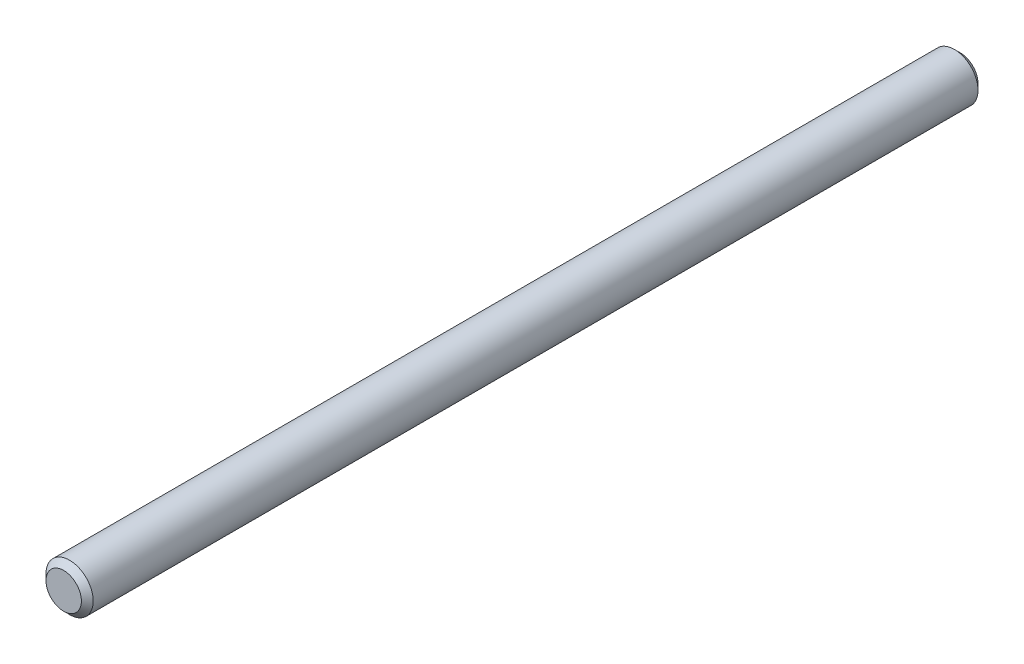
SolidWorks part; units mm, degrees
ref_plane "Ön Düzlem" through (0, 0, 0) normal (0, 0, 1) x (1, 0, 0)
ref_plane "Üst Düzlem" through (0, 0, 0) normal (0, 1, 0) x (1, 0, 0)
ref_plane "Sağ Düzlem" through (0, 0, 0) normal (1, 0, 0) x (0, 0, -1)
sketch "Sketch1" plane through (0, 0, 0) normal (0, 0, 1) x (1, 0, 0)
  circle A0 centre (0, 0) radius 3
  dimension "D1" = 6
extrude "Boss-Extrude1" add sketch "Sketch1" along normal blind 114
chamfer "Chamfer1" distance 0.75 angle 45 1 edges at (3, 0, 0)
chamfer "Chamfer2" distance 0.75 angle 45 1 edges at (3, 0, 114)
